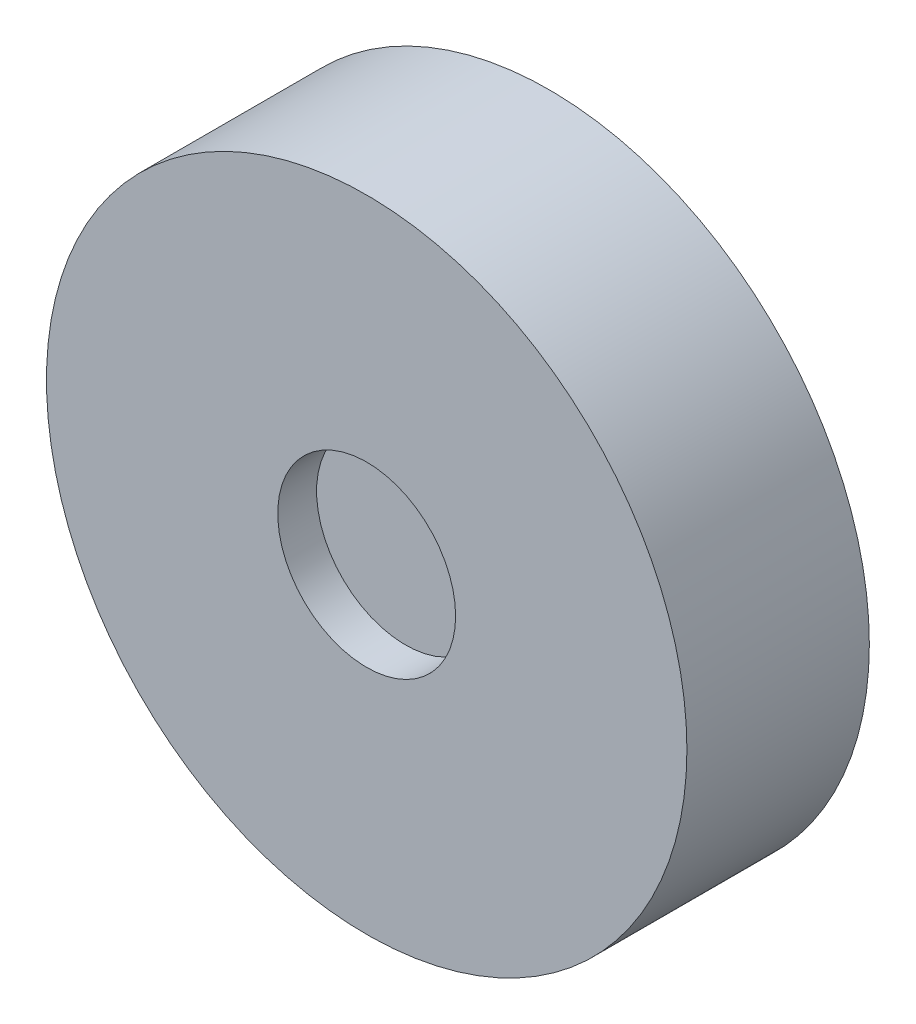
SolidWorks part; units mm, degrees
ref_plane "Front Plane" through (0, 0, 0) normal (0, 0, 1) x (1, 0, 0)
ref_plane "Top Plane" through (0, 0, 0) normal (0, 1, 0) x (1, 0, 0)
ref_plane "Right Plane" through (0, 0, 0) normal (1, 0, 0) x (0, 0, -1)
sketch "Sketch1" plane through (0, 0, 0) normal (0, 0, 1) x (1, 0, 0)
  circle A0 centre (-394.2929, -79.9041) radius 165
  dimension "D1" = 330
extrude "Boss-Extrude1" add sketch "Sketch1" along normal blind 94
sketch "Sketch2" plane through (0, 0, 0) normal (0, 0, 1) x (1, 0, 0)
  arc A149 (-467.6395, -22.1998) -> (-425.443, -59.1416) centre (-703.2521, -333.8976) cw
  arc A150 (-487.364, -67.8852) -> (-486.2804, -101.8476) centre (-392.2518, -81.849) ccw
  arc A151 (-487.364, -67.8852) -> (-432.3499, -78.7794) centre (-535.5617, -455.6296) cw
  arc A152 (-432.3499, -78.7794) -> (-432.8936, -90.9217) centre (-435.2942, -84.7309) cw
  arc A153 (-432.8936, -90.9217) -> (-486.2804, -101.8476) centre (-491.7883, 60.9598) cw
  arc A154 (-467.6395, -22.1998) -> (-483.6823, -52.154) centre (-392.2518, -81.849) ccw
  arc A155 (-431.985, -69.3853) -> (-483.6823, -52.154) centre (-407.0486, 91.5954) cw
  arc A156 (-425.443, -59.1416) -> (-431.985, -69.3853) centre (-430.9685, -62.8236) cw
  arc A157 (-427.7149, 7.5025) -> (-409.6425, -45.5882) centre (-787.6103, -144.6293) cw
  arc A158 (-427.7149, 7.5025) -> (-456.5854, -10.4171) centre (-392.2518, -81.849) ccw
  arc A159 (-420.4299, -51.1885) -> (-456.5854, -10.4171) centre (-318.344, 75.7566) cw
  arc A160 (-409.6425, -45.5882) -> (-420.4299, -51.1885) centre (-416.2688, -46.0141) cw
  arc A161 (-378.288, 13.2632) -> (-389.1822, -41.7509) centre (-766.0324, 61.4609) cw
  arc A162 (-378.288, 13.2632) -> (-412.2504, 12.1796) centre (-392.2518, -81.849) ccw
  arc A163 (-401.3245, -41.2072) -> (-412.2504, 12.1796) centre (-249.443, 17.6876) cw
  arc A164 (-389.1822, -41.7509) -> (-401.3245, -41.2072) centre (-395.1337, -38.8066) cw
  arc A165 (-332.6026, -6.4613) -> (-369.5444, -48.6578) centre (-644.3004, 229.1513) cw
  arc A166 (-332.6026, -6.4613) -> (-362.5568, 9.5815) centre (-392.2518, -81.849) ccw
  arc A167 (-379.7881, -42.1158) -> (-362.5568, 9.5815) centre (-218.8074, -67.0522) cw
  arc A168 (-369.5444, -48.6578) -> (-379.7881, -42.1158) centre (-373.2264, -43.1322) cw
  arc A169 (-302.9003, -46.3859) -> (-355.991, -64.4583) centre (-455.0321, 313.5095) cw
  arc A170 (-302.9003, -46.3859) -> (-320.8199, -17.5154) centre (-392.2518, -81.849) ccw
  arc A171 (-361.5913, -53.6709) -> (-320.8199, -17.5154) centre (-234.6462, -155.7568) cw
  arc A172 (-355.991, -64.4583) -> (-361.5913, -53.6709) centre (-356.4169, -57.832) cw
  arc A173 (-297.1396, -95.8128) -> (-352.1537, -84.9186) centre (-248.9419, 291.9316) cw
  arc A174 (-297.1396, -95.8128) -> (-298.2232, -61.8504) centre (-392.2518, -81.849) ccw
  arc A175 (-351.61, -72.7763) -> (-298.2232, -61.8504) centre (-292.7152, -224.6578) cw
  arc A176 (-352.1537, -84.9186) -> (-351.61, -72.7763) centre (-349.2094, -78.9671) cw
  arc A177 (-316.8641, -141.4981) -> (-359.0606, -104.5564) centre (-81.2515, 170.1996) cw
  arc A178 (-316.8641, -141.4981) -> (-300.8213, -111.544) centre (-392.2518, -81.849) ccw
  arc A179 (-352.5186, -94.3127) -> (-300.8213, -111.544) centre (-377.455, -255.2933) cw
  arc A180 (-359.0606, -104.5564) -> (-352.5186, -94.3127) centre (-353.535, -100.8744) cw
  arc A181 (-356.7887, -171.2005) -> (-374.8611, -118.1098) centre (3.1067, -19.0687) cw
  arc A182 (-356.7887, -171.2005) -> (-327.9182, -153.2809) centre (-392.2518, -81.849) ccw
  arc A183 (-364.0737, -112.5095) -> (-327.9182, -153.2809) centre (-466.1596, -239.4546) cw
  arc A184 (-374.8611, -118.1098) -> (-364.0737, -112.5095) centre (-368.2348, -117.6839) cw
  arc A185 (-406.2156, -176.9612) -> (-395.3214, -121.9471) centre (-18.4711, -225.1589) cw
  arc A186 (-406.2156, -176.9612) -> (-372.2532, -175.8776) centre (-392.2518, -81.849) ccw
  arc A187 (-383.1791, -122.4908) -> (-372.2532, -175.8776) centre (-535.0606, -181.3855) cw
  arc A188 (-395.3214, -121.9471) -> (-383.1791, -122.4908) centre (-389.3699, -124.8914) cw
  arc A189 (-451.9009, -157.2367) -> (-414.9592, -115.0402) centre (-140.2032, -392.8493) cw
  arc A190 (-451.9009, -157.2367) -> (-421.9468, -173.2795) centre (-392.2518, -81.849) ccw
  arc A191 (-404.7155, -121.5822) -> (-421.9468, -173.2795) centre (-565.6961, -96.6458) cw
  arc A192 (-414.9592, -115.0402) -> (-404.7155, -121.5822) centre (-411.2772, -120.5657) cw
  arc A193 (-481.6033, -117.3121) -> (-428.5126, -99.2397) centre (-329.4715, -477.2075) cw
  arc A194 (-481.6033, -117.3121) -> (-463.6837, -146.1826) centre (-392.2518, -81.849) ccw
  arc A195 (-422.9123, -110.0271) -> (-463.6837, -146.1826) centre (-549.8574, -7.9412) cw
  arc A196 (-428.5126, -99.2397) -> (-422.9123, -110.0271) centre (-428.0867, -105.866) cw
  point P92 (-392.2518, -81.849)
  dimension "D1" = 173.4443
extrude "Cut-Extrude7" cut sketch "Sketch2" along normal blind 44 draft 6
sketch "Sketch3" plane through (0, 0, 0) normal (0, 0, -1) x (-1, 0, 0)
  circle A0 centre (392.2518, -81.849) radius 113.5553
  circle A1 centre (392.2518, -81.849) radius 124.372
extrude "Cut-Extrude8" cut sketch "Sketch3" against normal blind 3
sketch "Sketch4" plane through (0, 0, 94) normal (0, 0, 1) x (1, 0, 0)
  circle A0 centre (-394.2929, -79.9041) radius 45.8248
  circle A1 centre (-394.2929, -79.9041) radius 165
  circle A2 centre (-394.2929, -79.9041) radius 165
  dimension "D2" = 91.6496
  dimension "D1" = 0
extrude "Cut-Extrude9" cut sketch "Sketch4" against normal blind 20 flip side to cut
